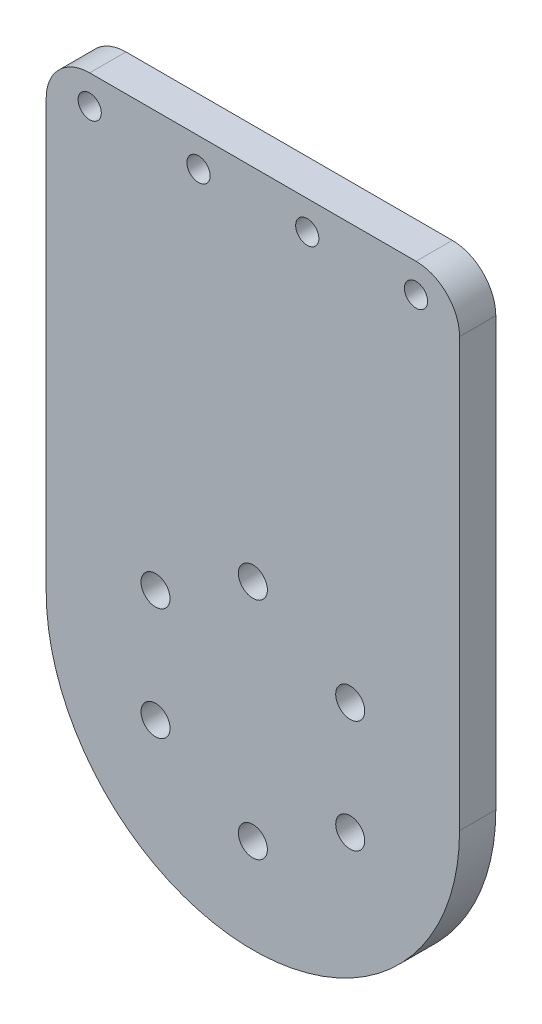
SolidWorks part; units mm, degrees
ref_plane "前基準面" through (0, 0, 0) normal (0, 0, 1) x (1, 0, 0)
ref_plane "上基準面" through (0, 0, 0) normal (0, 1, 0) x (1, 0, 0)
ref_plane "右基準面" through (0, 0, 0) normal (1, 0, 0) x (0, 0, -1)
sketch "草圖1" plane through (0, 0, 0) normal (0, 0, 1) x (1, 0, 0)
  line L8 (-28.5, 65) -> (28.5, 65)
  line L9 (-28.5, 65) -> (-28.5, 55)
  line L11 (28.5, 65) -> (28.5, 55.0205)
  line L12 (-28.5, 55) -> (-28.5, 0)
  line L13 (28.5, 55.0205) -> (28.5, 0)
  arc A0 (-21.4606, -18.7534) -> (21.4606, -18.7534) centre (0, 0) ccw
  arc A1 (-28.5, 0) -> (28.5, 0) centre (0, 0) ccw
  point P9 (0, -12.5)
  dimension "D2" = 65
  dimension "D6" = 57
extrude "填料-伸長1" add sketch "草圖1" along normal blind 5
sketch "草圖4" plane through (0, 0, 5) normal (0, 0, 1) x (1, 0, 0)
  circle A0 centre (0, -15.5) radius 2
  point P5 (0, 0)
  dimension "D4" = 4
  dimension "D1" = 15.5
extrude "除料-伸長2" cut sketch "草圖4" against normal up to next
sketch "草圖5" plane through (0, 0, 5) normal (0, 0, 1) x (1, 0, 0)
  line L0 (-997.4151, 61) -> (49002.5849, 61) construction
  line L3 (28.5, 65) -> (28.5, 0) construction
  line L4 (-28.5, 65) -> (28.5, 65) construction
  line L11 (28.5, 65) -> (-28.5, 65)
  line L12 (-28.5, 65) -> (-28.5, 0)
  line L14 (28.5, 0) -> (28.5, 65)
  line L16 (28.5, 65) -> (-28.5, 65)
  line L17 (-28.5, 65) -> (-28.5, 0)
  line L19 (28.5, 0) -> (28.5, 65)
  circle A0 centre (22.5, 61) radius 1.6
  circle A1 centre (7.5, 61) radius 1.6
  circle A2 centre (-7.5, 61) radius 1.6
  circle A3 centre (-22.5, 61) radius 1.6
  arc A5 (-28.5, 0) -> (28.5, 0) centre (0, 0) ccw
  arc A6 (-28.5, 0) -> (28.5, 0) centre (0, 0) ccw
  dimension "D2" = 3.2
  dimension "D1" = 6
  dimension "D3" = 4
  dimension "D5" = 15
  dimension "D6" = 0
  dimension "D4" = 4
extrude "除料-伸長3" cut sketch "草圖5" against normal through all flip side to cut
fillet "圓角1" radius 6 1 edges at (-28.5, 65, 2.5)
fillet "圓角2" radius 6 1 edges at (28.5, 65, 2.5)
pattern_circular "環狀複製排列1" count 6 over 360 about axis through (0, 0, 0) along (0, 0, 1) of "除料-伸長2"
